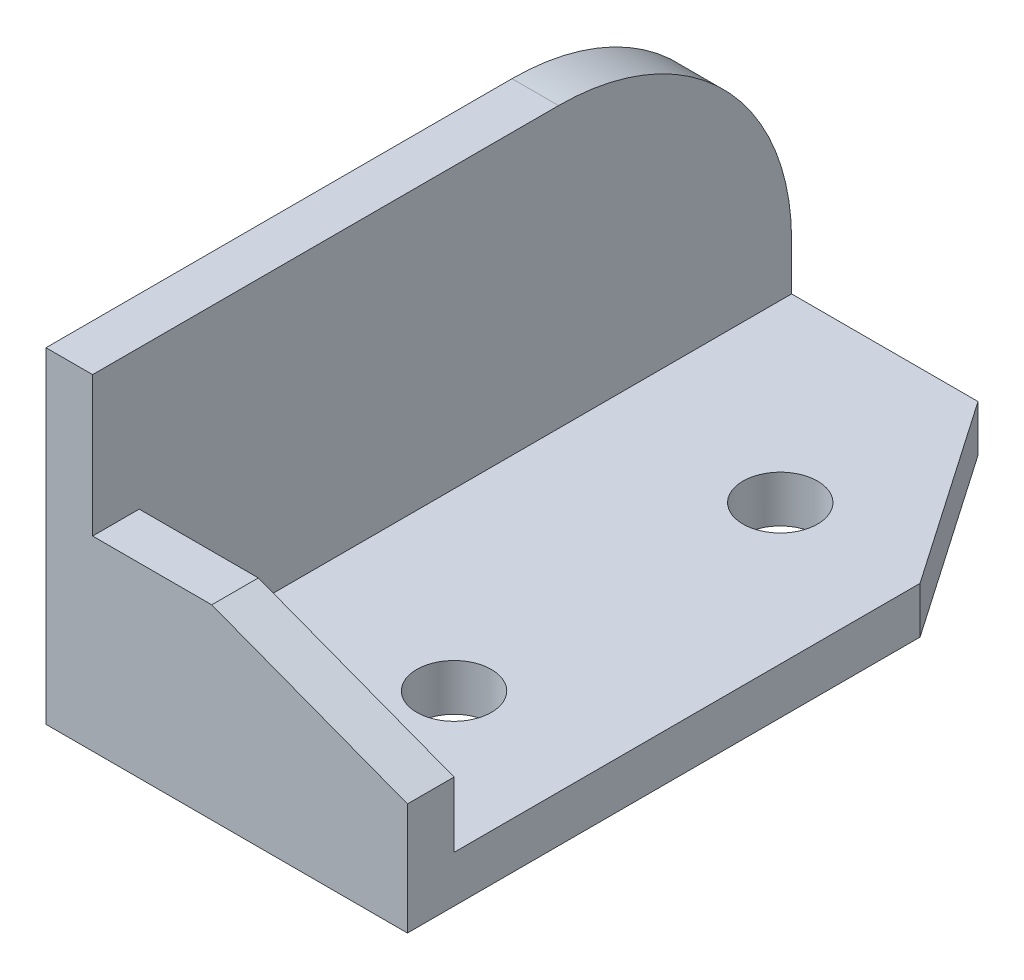
SolidWorks part; units mm, degrees
ref_plane "Płaszczyzna przednia" through (0, 0, 0) normal (0, 0, 1) x (1, 0, 0)
ref_plane "Płaszczyzna górna" through (0, 0, 0) normal (0, 1, 0) x (1, 0, 0)
ref_plane "Płaszczyzna prawa" through (0, 0, 0) normal (1, 0, 0) x (0, 0, -1)
sketch "Szkic1" plane through (0, 0, 0) normal (0, 0, 1) x (1, 0, 0)
  line L0 (0, 0) -> (38.7832, 0)
  line L1 (38.7832, 0) -> (38.7832, 5)
  line L2 (38.7832, 5) -> (5, 5)
  line L3 (5, 5) -> (5, 35)
  line L4 (5, 35) -> (0, 35)
  line L5 (0, 35) -> (0, 0)
  dimension "D1" = 35
  dimension "D2" = 5
  dimension "D3" = 38.7832
  dimension "D4" = 5
extrude "Dodanie-wyciągnięcie1" add sketch "Szkic1" against normal blind 75
fillet "Zaokrąglenie1" radius 25 1 edges at (2.5, 35, -75)
sketch "Szkic5" plane through (0, 0, 0) normal (0, -1, 0) x (1, 0, 0)
  line L0 (38.7832, -55) -> (25, -75)
  line L1 (38.7832, -75) -> (38.7832, 0) construction
  line L2 (0, -75) -> (38.7832, -75) construction
  line L3 (38.7832, -55) -> (38.7832, -75)
  line L4 (38.7832, -75) -> (25, -75)
  dimension "D1" = 25
  dimension "D2" = 55
extrude "Wytnij-wyciągnięcie1" cut sketch "Szkic5" against normal blind 75
sketch "Szkic6" plane through (0, 5, 0) normal (0, 1, 0) x (1, 0, 0)
  line L0 (38.7832, 55) -> (38.7832, 0) construction
  line L1 (38.7832, 0) -> (5, 0) construction
  circle A0 centre (23.7832, 55) radius 4
  circle A1 centre (23.7832, 20) radius 4
  point P6 (0, 0)
  dimension "D2" = 8
  dimension "D3" = 8
  dimension "D1" = 15
  dimension "D4" = 35
  dimension "D5" = 55
extrude "Wytnij-wyciągnięcie2" cut sketch "Szkic6" against normal blind 15
sketch "Szkic7" plane through (0, 5, 0) normal (0, 1, 0) x (1, 0, 0)
  line L1 (3.7832, 5) -> (38.7832, 5)
  line L2 (3.7832, 5) -> (3.7832, 0)
  line L3 (3.7832, 0) -> (38.7832, 0)
  line L4 (38.7832, 5) -> (38.7832, 0)
  dimension "D1" = 35
  dimension "D2" = 5
extrude "Dodanie-wyciągnięcie2" add sketch "Szkic7" along normal blind 15
sketch "Szkic8" plane through (0, 0, -5) normal (0, 0, -1) x (-1, 0, 0)
  line L0 (-38.7832, 12) -> (-17.7832, 20)
  line L1 (-38.7832, 20) -> (-38.7832, 5) construction
  line L2 (-38.7832, 20) -> (-5, 20) construction
  line L3 (-17.7832, 20) -> (-38.7832, 20)
  line L4 (-38.7832, 20) -> (-38.7832, 12)
  dimension "D1" = 21
  dimension "D2" = 8
extrude "Wytnij-wyciągnięcie3" cut sketch "Szkic8" against normal blind 15
